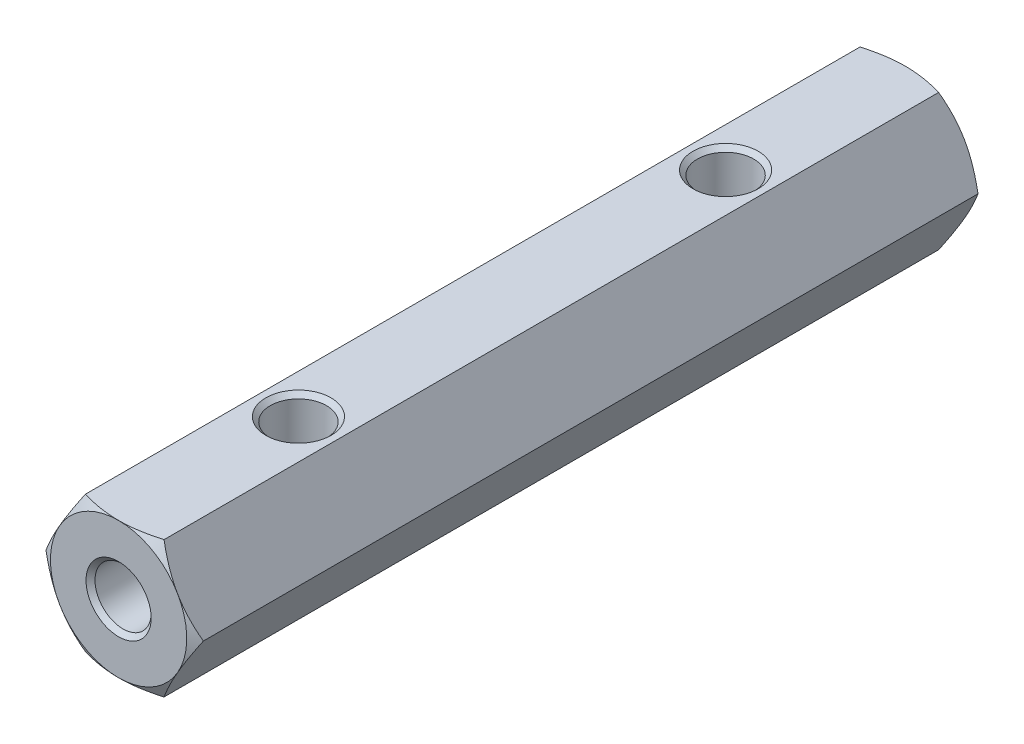
SolidWorks part; units mm, degrees
ref_plane "前视基准面" through (0, 0, 0) normal (0, 0, 1) x (1, 0, 0)
ref_plane "上视基准面" through (0, 0, 0) normal (0, 1, 0) x (1, 0, 0)
ref_plane "右视基准面" through (0, 0, 0) normal (1, 0, 0) x (0, 0, -1)
sketch "草图1" plane through (0, 0, 0) normal (0, 0, 1) x (1, 0, 0)
  line L0 (0, 0) -> (1958.9043, 0) construction
  line L1 (3.5, 0) -> (1.75, 3.0311)
  line L2 (1.75, 3.0311) -> (-1.75, 3.0311)
  line L3 (-1.75, 3.0311) -> (-3.5, 0)
  line L4 (-3.5, 0) -> (-1.75, -3.0311)
  line L5 (-1.75, -3.0311) -> (1.75, -3.0311)
  line L6 (1.75, -3.0311) -> (3.5, 0)
  line L7 (0, 0) -> (0, 1958.9043) construction
  circle A0 centre (0, 0) radius 3.0311 construction
  point P1 (0, 0)
  dimension "D1" = 7
extrude "凸台-拉伸1" add sketch "草图1" along normal mid plane 35
sketch "草图2" plane through (0, 0, 17.5) normal (0, 0, 1) x (1, 0, 0)
  line L0 (3.5, 0) -> (1.75, 3.0311) construction
  circle A0 centre (0, 0) radius 3.0311
extrude "切除-拉伸1" cut sketch "草图2" against normal through all draft 60 flip side to cut
hole_wizard "M3 螺纹孔1" positions "草图5" profile "草图4" tap size "M3" standard "GB" end condition through all
sketch "草图5" plane through (0, 0, 17.5) normal (0, 0, 1) x (1, 0, 0)
  point P0 (0, 0)
sketch "草图4" plane through (0, 0, 17.5) normal (1, 0, 0) x (0, -1, 0)
  line L0 (0, 0) -> (0, 35)
  line L1 (0, 35) -> (1.25, 35)
  line L2 (1.25, 35) -> (1.25, 0)
  line L5 (1.25, 0) -> (0, 0)
  line L11 (0, -6.35) -> (0, 107.95) construction
  dimension "通孔螺纹孔钻头直径" = 2.5
  dimension "通孔螺纹孔钻头深度" = 35
cosmetic thread "孔螺蚊线1" parameters "D2"=3
hole_wizard "M3 螺纹孔2" positions "草图6" profile "草图7" tap size "M3" standard "GB" end condition through all
sketch "草图6" plane through (0, 3.0311, 0) normal (0, 1, 0) x (1, 0, 0)
  point P0 (0, -9.5)
  dimension "D1" = 9.5
sketch "草图7" plane through (0, 3.0311, 9.5) normal (1, 0, 0) x (0, 0, 1)
  line L0 (0, 0) -> (0, 6.0622)
  line L1 (0, 6.0622) -> (1.25, 6.0622)
  line L2 (1.25, 6.0622) -> (1.25, 0)
  line L5 (1.25, 0) -> (0, 0)
  line L11 (0, -6.35) -> (0, 107.95) construction
  dimension "通孔螺纹孔钻头直径" = 2.5
  dimension "通孔螺纹孔钻头深度" = 6.0622
cosmetic thread "孔螺蚊线5" parameters "D2"=3
mirror "镜向1" about plane through (0, 0, 0) normal (0, 0, 1) of "M3 螺纹孔1", "M3 螺纹孔2", "切除-拉伸1"
cosmetic thread "孔螺蚊线6" parameters "D2"=3
chamfer "倒角1" distance 0.2 angle 45 6 edges at (0, -3.0311, 10.75) (1.25, 0, 17.5) (0, 3.0311, 10.75) (0, 3.0311, -8.25) (1.25, 0, -17.5) (0, -3.0311, -8.25)
